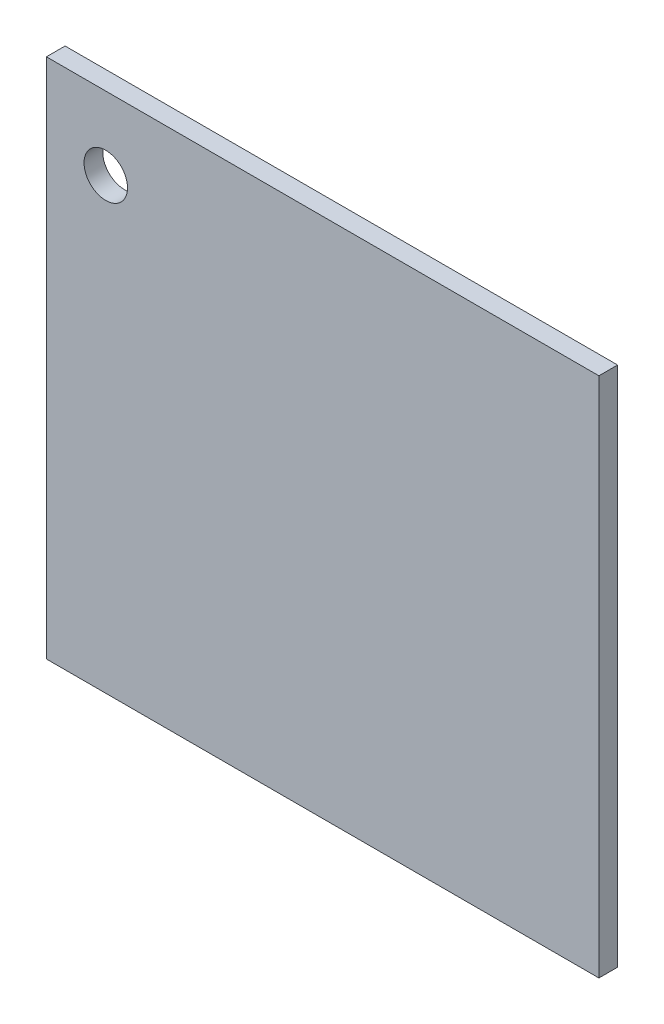
SolidWorks part; units mm, degrees
ref_plane "Front Plane" through (0, 0, 0) normal (0, 0, 1) x (1, 0, 0)
ref_plane "Top Plane" through (0, 0, 0) normal (0, 1, 0) x (1, 0, 0)
ref_plane "Right Plane" through (0, 0, 0) normal (1, 0, 0) x (0, 0, -1)
sketch "Sketch1" plane through (0, 0, 0) normal (0, 0, 1) x (1, 0, 0)
  line L1 (-230.0073, 190.8461) -> (65.6115, 190.8461)
  line L2 (-230.0073, 190.8461) -> (-230.0073, -88.203)
  line L3 (-230.0073, -88.203) -> (65.6115, -88.203)
  line L4 (65.6115, 190.8461) -> (65.6115, -88.203)
  line L5 (-230.0073, 190.8461) -> (65.6115, -88.203) construction
  line L6 (-230.0073, -88.203) -> (65.6115, 190.8461) construction
  point P0 (-82.1979, 51.3216)
extrude "Boss-Extrude1" add sketch "Sketch1" along normal blind 10
sketch "Sketch2" plane through (0, 0, 10) normal (0, 0, 1) x (1, 0, 0)
  circle A0 centre (-198.2452, 151.7893) radius 11.6329
extrude "Cut-Extrude1" cut sketch "Sketch2" against normal blind 10
sketch "Sketch3" plane through (0, 0, 10) normal (0, 0, 1) x (1, 0, 0)
  line L0 (-89.5882, 198.5278) -> (-89.5882, -100.3112) construction
  line L1 (-274.1453, 49.1083) -> (126.5274, 49.1083) construction
